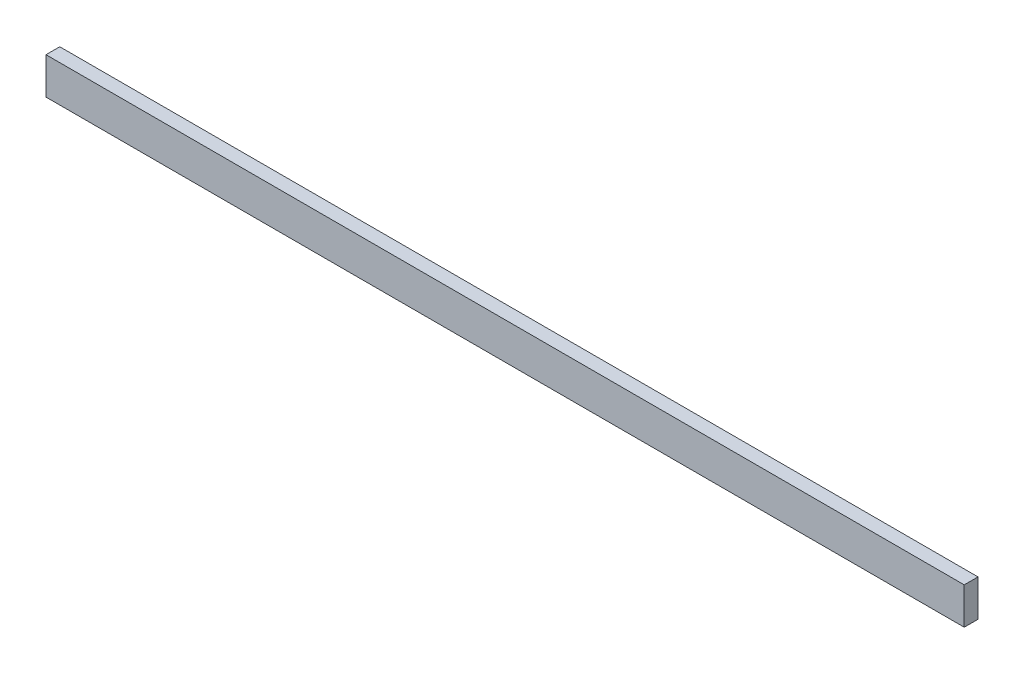
SolidWorks part; units mm, degrees
ref_plane "Front Plane" through (0, 0, 0) normal (0, 0, 1) x (1, 0, 0)
ref_plane "Top Plane" through (0, 0, 0) normal (0, 1, 0) x (1, 0, 0)
ref_plane "Right Plane" through (0, 0, 0) normal (1, 0, 0) x (0, 0, -1)
sketch "Sketch1" plane through (0, 0, 0) normal (1, 0, 0) x (0, 0, -1)
  line L1 (0, 0) -> (75, 0)
  line L2 (0, 0) -> (0, 200)
  line L3 (0, 200) -> (75, 200)
  line L4 (75, 0) -> (75, 200)
  dimension "D1" = 200
  dimension "D2" = 75
extrude "Boss-Extrude1" add sketch "Sketch1" along normal blind 5000
